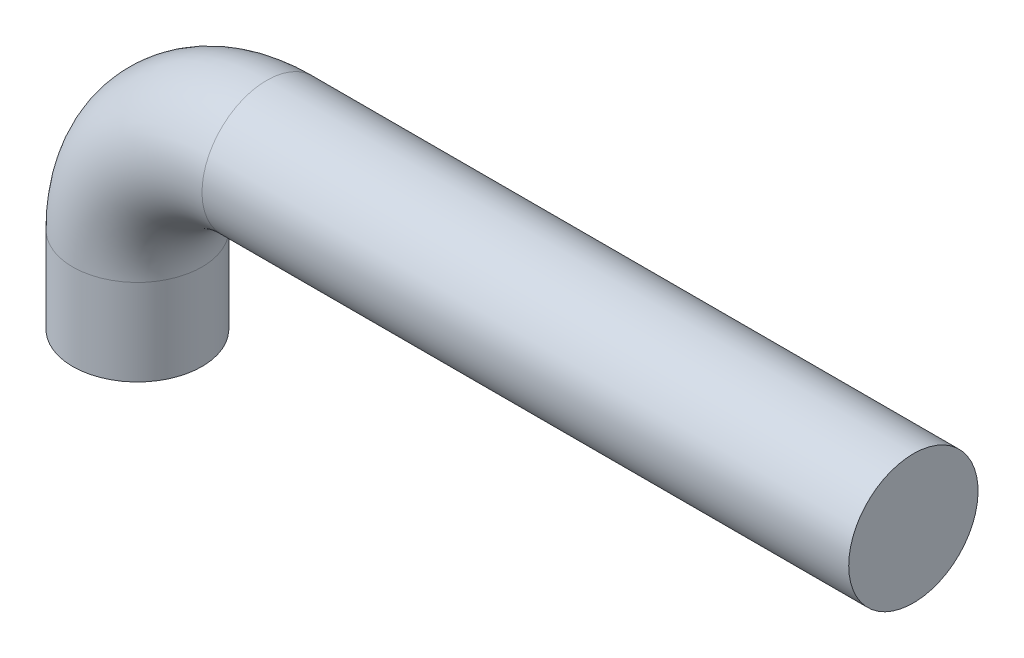
SolidWorks part; units mm, degrees
ref_plane "Alzado" through (0, 0, 0) normal (0, 0, 1) x (1, 0, 0)
ref_plane "Planta" through (0, 0, 0) normal (0, 1, 0) x (1, 0, 0)
ref_plane "Vista lateral" through (0, 0, 0) normal (1, 0, 0) x (0, 0, -1)
sketch "Croquis2" plane through (0, 0, 0) normal (0, 0, 1) x (1, 0, 0)
  line L0 (0, 0) -> (0, 4)
  line L1 (6, 10) -> (36, 10)
  arc A0 (0, 4) -> (6, 10) centre (6, 4) cw
  point P5 (4.9584, 5.0416)
  point P6 (5.8493, 4.1507)
  point P8 (0, 0)
  dimension "D3" = 6
  dimension "D1" = 30
  dimension "D2" = 10
sketch "Croquis3" plane through (0, 0, 0) normal (0, 1, 0) x (1, 0, 0)
  circle A0 centre (0, 0) radius 3
  dimension "D1" = 6
sweep "Barrer1" add profiles "Croquis3" path "Croquis2"
